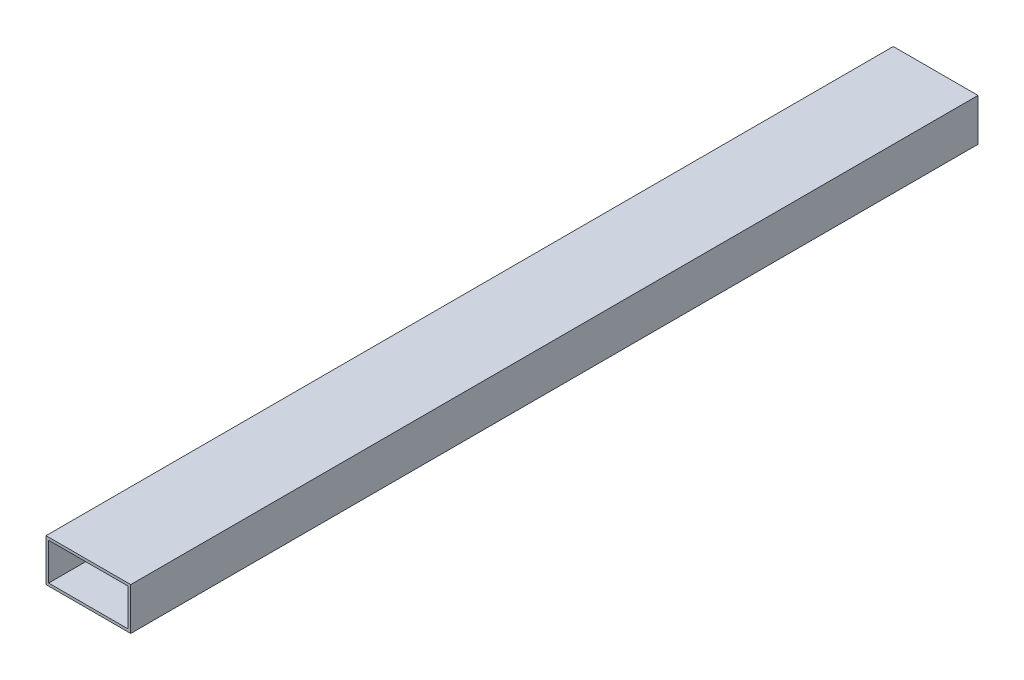
SolidWorks part; units mm, degrees
ref_plane "Front Plane" through (0, 0, 0) normal (0, 0, 1) x (1, 0, 0)
ref_plane "Top Plane" through (0, 0, 0) normal (0, 1, 0) x (1, 0, 0)
ref_plane "Right Plane" through (0, 0, 0) normal (1, 0, 0) x (0, 0, -1)
sketch "Sketch1" plane through (0, 0, 0) normal (0, 0, 1) x (1, 0, 0)
  line L0 (1.5875, 23.8125) -> (49.2125, 23.8125)
  line L1 (0, 0) -> (50.8, 0)
  line L2 (0, 0) -> (0, 25.4)
  line L3 (0, 25.4) -> (50.8, 25.4)
  line L4 (50.8, 0) -> (50.8, 25.4)
  line L5 (49.2125, 1.5875) -> (49.2125, 23.8125)
  line L6 (1.5875, 1.5875) -> (49.2125, 1.5875)
  line L7 (1.5875, 1.5875) -> (1.5875, 23.8125)
  dimension "D1" = 25.4
  dimension "D2" = 50.8
  dimension "D3" = 1.5875
extrude "Boss-Extrude1" add sketch "Sketch1" along normal blind 508
